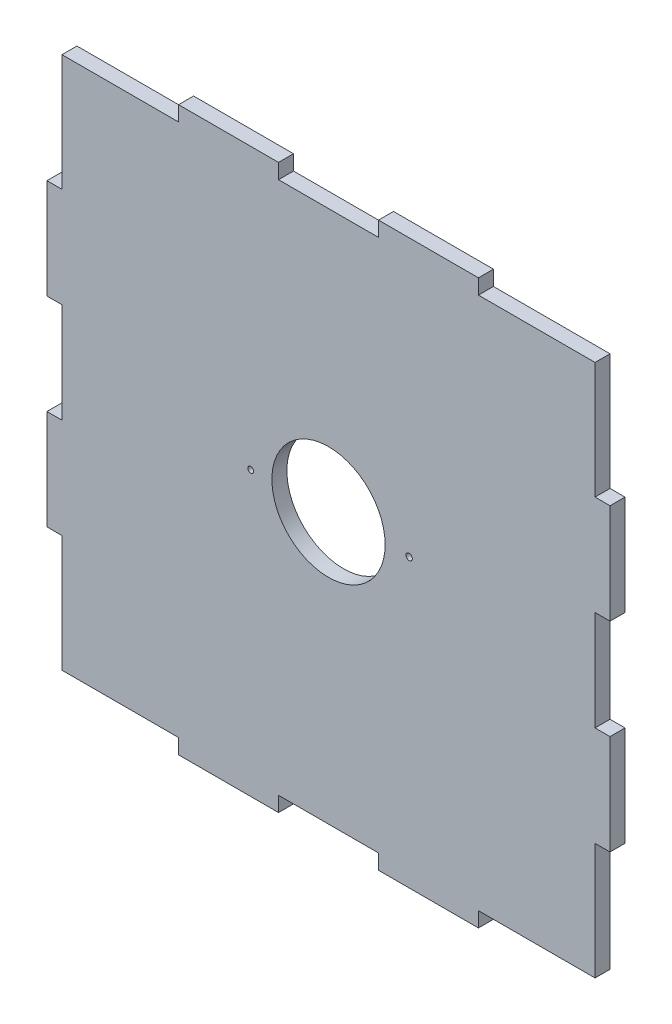
SolidWorks part; units mm, degrees
ref_plane "Front Plane" through (0, 0, 0) normal (0, 0, 1) x (1, 0, 0)
ref_plane "Top Plane" through (0, 0, 0) normal (0, 1, 0) x (1, 0, 0)
ref_plane "Right Plane" through (0, 0, 0) normal (1, 0, 0) x (0, 0, -1)
sketch "Sketch2" plane through (0, 0, 0) normal (0, 0, 1) x (1, 0, 0)
  line L2 (-148.1553, 60) -> (-148.1553, 0)
  line L4 (189.8447, 60) -> (189.8447, 0)
  line L5 (180.8447, 130) -> (180.8447, 60)
  line L7 (-139.1553, 130) -> (-139.1553, 60)
  line L8 (-39.1553, 139) -> (-39.1553, -199) construction
  line L9 (-69.1553, 139) -> (-69.1553, 130)
  line L10 (50.8447, 139) -> (50.8447, 130)
  line L11 (-9.1553, 139) -> (-9.1553, 130)
  line L12 (110.8447, 139) -> (110.8447, 130)
  line L13 (-143.2705, -30) -> (155.7149, -30) construction
  line L15 (50.8447, -199) -> (50.8447, -190)
  line L16 (-9.1553, -199) -> (-9.1553, -190)
  line L17 (-69.1553, -199) -> (-69.1553, -190)
  line L18 (-148.1553, 60) -> (-139.1553, 60)
  line L19 (-148.1553, -120) -> (-139.1553, -120)
  line L20 (-148.1553, 0) -> (-139.1553, 0)
  line L21 (-148.1553, -60) -> (-139.1553, -60)
  line L23 (-148.1553, 139) -> (-148.1553, -199) construction
  line L24 (-139.1553, 0) -> (-139.1553, -60)
  line L25 (-148.1553, -60) -> (-148.1553, -120)
  line L27 (-148.1553, 139) -> (189.8447, 139) construction
  line L30 (-139.1553, 130) -> (180.8447, 130) construction
  line L31 (-139.1553, 130) -> (-139.1553, -190) construction
  line L32 (-139.1553, -190) -> (180.8447, -190) construction
  line L35 (-148.1553, -199) -> (189.8447, -199) construction
  line L38 (180.8447, 60) -> (189.8447, 60)
  line L39 (-139.1553, -120) -> (-139.1553, -190)
  line L40 (189.8447, 0) -> (180.8447, 0)
  line L41 (189.8447, -60) -> (180.8447, -60)
  line L42 (180.8447, -120) -> (189.8447, -120)
  line L44 (189.8447, 139) -> (189.8447, -199) construction
  line L45 (180.8447, -120) -> (180.8447, -190)
  line L46 (180.8447, 130) -> (180.8447, -190) construction
  line L47 (189.8447, -60) -> (189.8447, -120)
  line L48 (180.8447, 0) -> (180.8447, -60)
  line L49 (-69.1553, 130) -> (-139.1553, 130)
  line L50 (-9.1553, 130) -> (50.8447, 130)
  line L51 (50.8447, 139) -> (110.8447, 139)
  line L52 (110.8447, 130) -> (180.8447, 130)
  line L53 (-9.1553, 139) -> (-69.1553, 139)
  line L54 (-9.1553, -199) -> (-69.1553, -199)
  line L55 (50.8447, -199) -> (110.8447, -199)
  line L56 (-9.1553, -190) -> (50.8447, -190)
  line L58 (-9.1553, -199) -> (-9.1553, -190)
  line L59 (50.8447, -199) -> (50.8447, -190)
  line L60 (-69.1553, -199) -> (-69.1553, -190)
  line L61 (-69.1553, -190) -> (-139.1553, -190)
  line L62 (110.8447, -190) -> (180.8447, -190)
  line L63 (110.8447, -190) -> (110.8447, -199)
  line L64 (-148.1553, 30) -> (189.8447, 30) construction
  line L65 (20.8447, 30) -> (20.8447, 130) construction
  point P10 (-9.1553, 134.5)
  point P32 (-143.6553, 0)
  point P38 (-143.6553, -60)
  point P49 (80.8447, 139)
  dimension "D1" = 30
  dimension "D2" = 338
  dimension "D4" = 60
  dimension "D5" = 30
  dimension "D6" = 60
  dimension "D7" = 30
  dimension "D8" = 60
  dimension "D9" = 60
  dimension "D10" = 320
  dimension "D11" = 338
  dimension "D12" = 320
  dimension "D13" = 320
  dimension "D14" = 70
  dimension "D15" = 60
  dimension "D3" = 9
extrude "Boss-Extrude1" add sketch "Sketch2" along normal blind 9 contours L63 L62 L45 L42 L47 L41 L48 L40 L4 L38 L5 L52 L12 L51 L10 L50 L11 L53 L9 L49 L7 L18 L2 L20 L24 L21 L25 L19 L39 L61 L17 L54 L16 L56 L15 L55
sketch "Sketch3" plane through (0, 0, 9) normal (0, 0, 1) x (1, 0, 0)
  line L0 (20.8447, -190) -> (20.8447, -27.75) construction
  line L1 (-9.1553, -190) -> (50.8447, -190) construction
  circle A0 centre (20.8447, -27.75) radius 34
  dimension "D1" = 162.25
  dimension "D2" = 68
extrude "Cut-Extrude1" cut sketch "Sketch3" against normal blind 10
sketch "Sketch4" plane through (0, 0, 9) normal (0, 0, 1) x (1, 0, 0)
  circle A0 centre (69.2477, -26.8716) radius 1.9082
  circle A1 centre (-25.8197, -29.1588) radius 1.75
extrude "Cut-Extrude2" cut sketch "Sketch4" against normal through all
